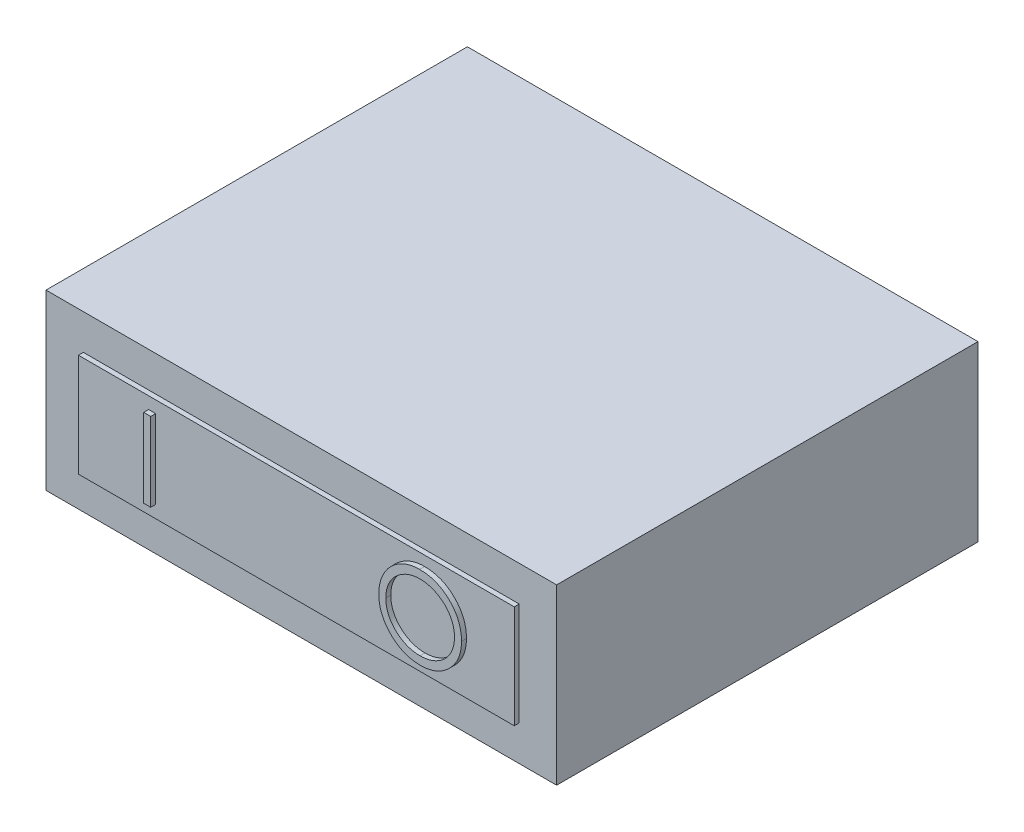
SolidWorks part; units mm, degrees
ref_plane "Front Plane" through (0, 0, 0) normal (0, 0, 1) x (1, 0, 0)
ref_plane "Top Plane" through (0, 0, 0) normal (0, 1, 0) x (1, 0, 0)
ref_plane "Right Plane" through (0, 0, 0) normal (1, 0, 0) x (0, 0, -1)
sketch "Sketch1" plane through (0, 0, 0) normal (0, 1, 0) x (1, 0, 0)
  line L1 (-10.3, 8.5) -> (10.3, 8.5)
  line L2 (-10.3, 8.5) -> (-10.3, -8.5)
  line L3 (-10.3, -8.5) -> (10.3, -8.5)
  line L4 (10.3, 8.5) -> (10.3, -8.5)
  line L5 (-10.3, 8.5) -> (10.3, -8.5) construction
  line L6 (-10.3, -8.5) -> (10.3, 8.5) construction
  point P0 (0, 0)
  dimension "D1" = 20.6
  dimension "D2" = 17
extrude "Boss-Extrude1" add sketch "Sketch1" along normal blind 7
sketch "Sketch2" plane through (0, 0, 8.5) normal (0, 0, 1) x (1, 0, 0)
  line L1 (-8.7912, 5.5775) -> (8.7912, 5.5775)
  line L2 (-8.7912, 5.5775) -> (-8.7912, 1.4225)
  line L3 (-8.7912, 1.4225) -> (8.7912, 1.4225)
  line L4 (8.7912, 5.5775) -> (8.7912, 1.4225)
  line L5 (-8.7912, 5.5775) -> (8.7912, 1.4225) construction
  line L6 (-8.7912, 1.4225) -> (8.7912, 5.5775) construction
  point P0 (0, 3.5)
extrude "Boss-Extrude2" add sketch "Sketch2" along normal blind 0.2
sketch "Sketch3" plane through (0, 0, 8.7) normal (0, 0, 1) x (1, 0, 0)
  text T0 "I       O"
extrude "Boss-Extrude3" add sketch "Sketch3" along normal blind 0.2
